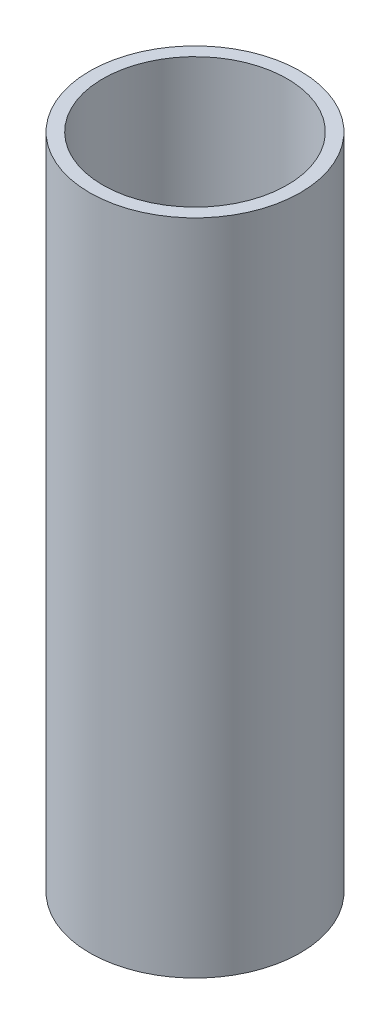
SolidWorks part; units mm, degrees
ref_plane "Спереди" through (0, 0, 0) normal (0, 0, 1) x (1, 0, 0)
ref_plane "Сверху" through (0, 0, 0) normal (0, 1, 0) x (1, 0, 0)
ref_plane "Справа" through (0, 0, 0) normal (1, 0, 0) x (0, 0, -1)
sketch "Эскиз1" plane through (0, 0, 0) normal (0, 1, 0) x (1, 0, 0)
  circle A0 centre (0, 0) radius 8
  circle A1 centre (0, 0) radius 7
  dimension "D1" = 16
  dimension "D2" = 1
extrude "Бобышка-Вытянуть1" add sketch "Эскиз1" along normal blind 50
